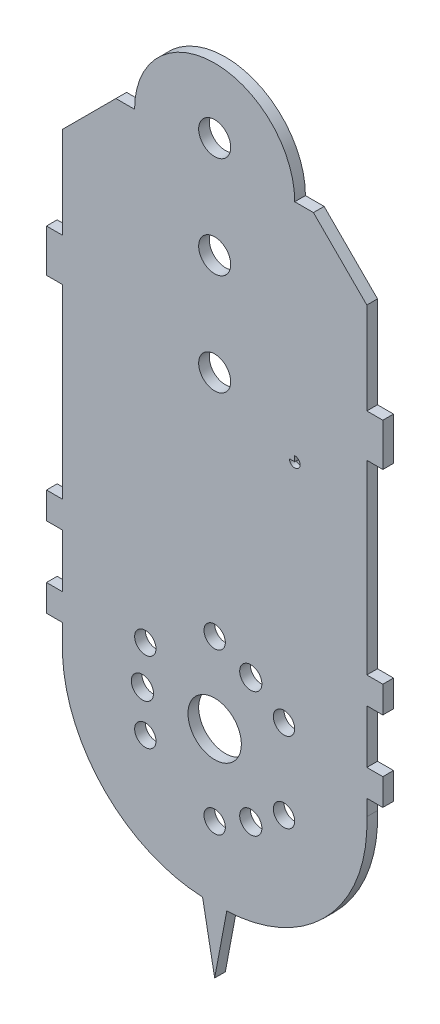
SolidWorks part; units mm, degrees
ref_plane "前视基准面" through (0, 0, 0) normal (0, 0, 1) x (1, 0, 0)
ref_plane "上视基准面" through (0, 0, 0) normal (0, 1, 0) x (1, 0, 0)
ref_plane "右视基准面" through (0, 0, 0) normal (1, 0, 0) x (0, 0, -1)
sketch "草图1" plane through (0, 0, 0) normal (0, 0, 1) x (1, 0, 0)
  line L133 (-2.2662, -70.5745) -> (-2.2662, -75.5745) construction
  line L156 (26.2338, -52.5745) -> (29.2338, -52.5745)
  line L158 (29.2338, -62.5745) -> (26.2338, -62.5745)
  line L220 (26.2338, -67.5745) -> (26.2338, -70.5745)
  line L223 (26.2338, -54.5745) -> (26.2338, -57.5745)
  line L224 (-30.7662, -54.5745) -> (-30.7662, -57.5745)
  line L227 (26.2338, -54.5745) -> (26.2338, -52.5745)
  line L242 (29.2338, -62.5745) -> (29.2338, -67.5745)
  line L251 (29.2338, -52.5745) -> (29.2338, -47.5745)
  line L252 (29.2338, -47.5745) -> (26.2338, -47.5745)
  line L258 (26.2338, -62.5745) -> (26.2338, -57.5745)
  line L260 (29.2338, -67.5745) -> (26.2338, -67.5745)
  line L269 (-2.2662, 6.2455) -> (-2.2662, -12.7545) construction
  line L270 (-30.7662, -62.5745) -> (-30.7662, -57.5745)
  line L272 (-33.7662, -47.5745) -> (-30.7662, -47.5745)
  line L273 (-33.7662, -52.5745) -> (-33.7662, -47.5745)
  line L285 (-30.7662, -54.5745) -> (-30.7662, -52.5745)
  line L286 (-33.7662, -62.5745) -> (-30.7662, -62.5745)
  line L287 (-30.7662, -52.5745) -> (-33.7662, -52.5745)
  line L288 (-33.7662, -62.5745) -> (-33.7662, -67.5745)
  line L289 (-33.7662, -67.5745) -> (-30.7662, -67.5745)
  line L290 (-30.7662, -67.5745) -> (-30.7662, -70.5745)
  line L292 (-2.2662, -12.7545) -> (-2.2662, -70.5745) construction
  line L293 (-2.2662, 6.2455) -> (-2.2662, 25.2455) construction
  line L312 (-30.7662, 12.4255) -> (-30.7662, -4.6545)
  line L313 (26.2338, -4.6545) -> (26.2338, -4.7545)
  line L314 (26.2338, -4.7545) -> (29.2338, -4.7545)
  line L315 (29.2338, -4.7545) -> (29.2338, -12.7545)
  line L316 (29.2338, -12.7545) -> (26.2338, -12.7545)
  line L317 (26.2338, -12.7545) -> (26.2338, -47.5745)
  line L319 (-33.7662, -12.7545) -> (-30.7662, -12.7545)
  line L320 (-33.7662, -4.7545) -> (-33.7662, -12.7545)
  line L321 (-30.7662, -4.7545) -> (-33.7662, -4.7545)
  line L322 (-30.7662, -4.6545) -> (-30.7662, -4.7545)
  line L323 (-30.7662, -12.7545) -> (-30.7662, -47.5745)
  line L326 (-20.7662, 22.4255) -> (-17.2662, 22.4255)
  line L327 (16.2338, 22.4255) -> (12.7338, 22.4255)
  line L328 (26.2338, 12.4255) -> (26.2338, -4.6545)
  line L329 (-30.7662, 12.4255) -> (-20.7662, 22.4255)
  line L330 (16.2338, 22.4255) -> (26.2338, 12.4255)
  line L331 (-2.2662, -110.9843) -> (-2.2662, -98.9843) construction
  line L332 (-2.2662, -110.9843) -> (0, -98.9843)
  line L333 (-2.2662, -110.9843) -> (-4.5323, -98.9843)
  circle A15 centre (-2.2662, -70.5745) radius 15 construction
  circle A16 centre (-2.2662, -70.5745) radius 13.53 construction
  circle A17 centre (-2.2662, -85.5717) radius 2
  circle A18 centre (-15.2541, -78.0731) radius 2
  circle A19 centre (-15.2541, -63.0759) radius 2
  circle A20 centre (-2.2662, -55.5773) radius 2
  circle A21 centre (10.7218, -63.0759) radius 2
  circle A22 centre (10.7218, -78.0731) radius 2
  circle A23 centre (-15.7962, -70.5745) radius 2.08
  circle A24 centre (4.4988, -58.8572) radius 2.08
  circle A25 centre (4.4988, -82.2918) radius 2.08
  circle A26 centre (-2.2662, -70.5745) radius 5
  circle A37 centre (-2.2662, -12.7545) radius 3
  circle A39 centre (-2.2662, 6.2455) radius 3
  circle A40 centre (-2.2662, 25.2455) radius 3
  arc A41 (-17.2662, 22.4255) -> (12.7338, 22.4255) centre (-2.2662, 22.4255) cw
  arc A42 (0, -98.9843) -> (26.2338, -70.5745) centre (-1.088, -71.6625) ccw
  arc A43 (-4.5323, -98.9843) -> (-30.7662, -70.5745) centre (-3.4444, -71.6625) cw
  dimension "D2" = 6
extrude "凸台-拉伸1" add sketch "草图1" along normal blind 2
sketch "草图2" plane through (0, 0, 2) normal (0, 0, 1) x (1, 0, 0)
  line L0 (-2.2662, -12.7545) -> (-2.2662, -19.7493)
  line L1 (-2.2662, -19.7493) -> (12.7338, -19.7493)
  line L2 (12.7338, -19.7493) -> (12.7338, -4.7493)
  circle A0 centre (12.7338, -19.7493) radius 1
  point P0 (-2.2662, -12.7545)
extrude "切除-拉伸1" cut sketch "草图2" against normal blind 1 contours L1 A0 L2
sketch "草图3" plane through (0, 0, 2) normal (0, 0, 1) x (1, 0, 0)
  line L0 (-2.2662, -70.5745) -> (11.0073, -70.5745) construction
  line L1 (-2.2662, -70.5745) -> (-2.2662, -80.5531) construction
